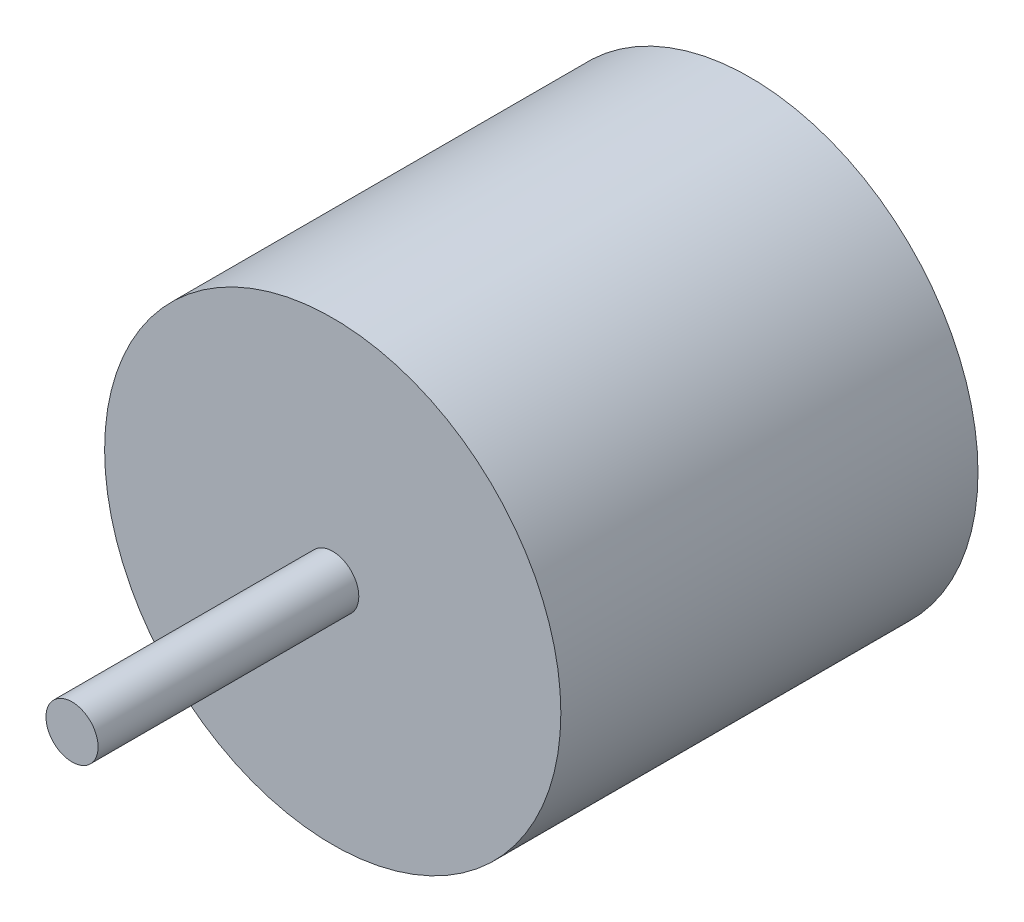
SolidWorks part; units mm, degrees
ref_plane "Plan de face" through (0, 0, 0) normal (0, 0, 1) x (1, 0, 0)
ref_plane "Plan de dessus" through (0, 0, 0) normal (0, 1, 0) x (1, 0, 0)
ref_plane "Plan de droite" through (0, 0, 0) normal (1, 0, 0) x (0, 0, -1)
sketch "Esquisse1" plane through (0, 0, 0) normal (0, 0, 1) x (1, 0, 0)
  circle A0 centre (0, 0) radius 17.5
extrude "Boss.-Extru.1" add sketch "Esquisse1" along normal blind 32
sketch "Esquisse2" plane through (0, 0, 32) normal (0, 0, 1) x (1, 0, 0)
  circle A0 centre (0, 0) radius 2
  dimension "D1" = 4
extrude "Boss.-Extru.2" add sketch "Esquisse2" along normal blind 20
